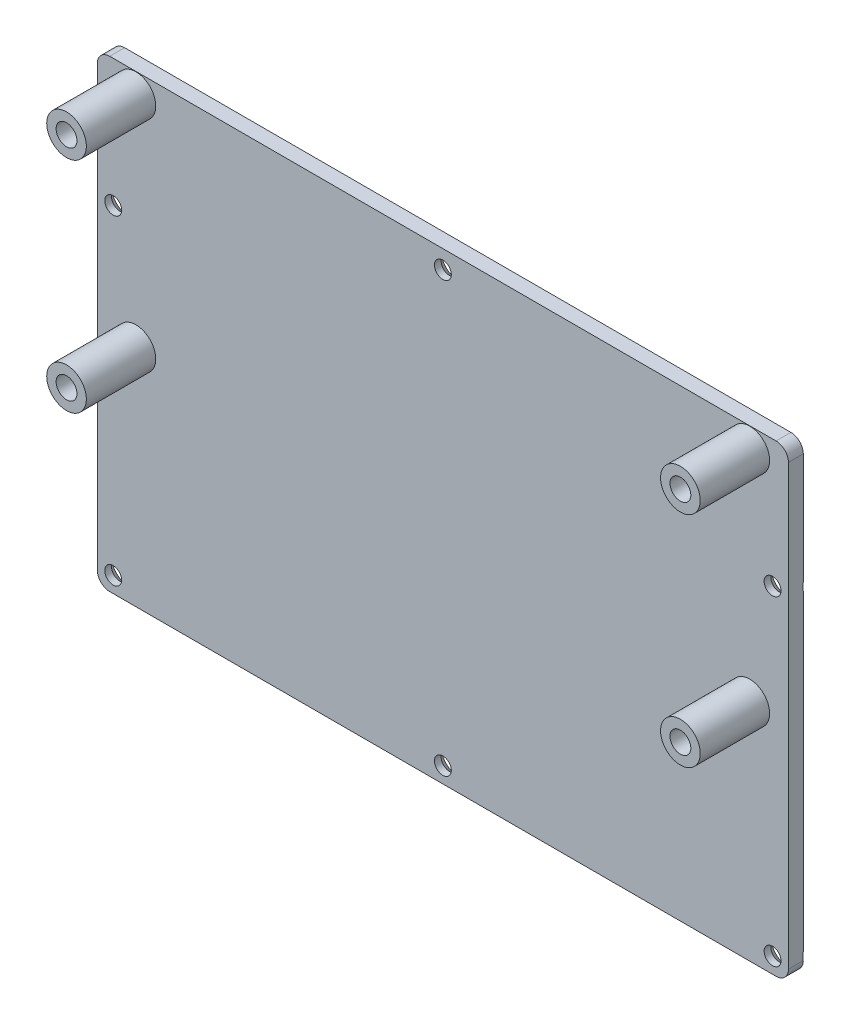
SolidWorks part; units mm, degrees
ref_plane "Front Plane" through (0, 0, 0) normal (0, 0, 1) x (1, 0, 0)
ref_plane "Top Plane" through (0, 0, 0) normal (0, 1, 0) x (1, 0, 0)
ref_plane "Right Plane" through (0, 0, 0) normal (1, 0, 0) x (0, 0, -1)
ref_plane "Plane1" through (0, 0, 0) normal (0, 0, -1) x (-1, 0, 0)
sketch "Sketch1" plane through (0, 0, 0) normal (0, 0, -1) x (-1, 0, 0)
  line L0 (-69.7, 93.82) -> (-69.7, 71.4262)
  line L1 (-69.7, 71.4262) -> (-69.7, 69.8138)
  line L2 (-69.7, 69.8138) -> (-69.7, 6.8062)
  line L3 (-69.7, 6.8062) -> (-69.7, 5.3)
  line L4 (-67.2, 2.8) -> (-65.6938, 2.8)
  line L5 (-65.6938, 2.8) -> (-0.8062, 2.8)
  line L6 (-0.8062, 2.8) -> (0.8062, 2.8)
  line L7 (0.8062, 2.8) -> (65.6938, 2.8)
  line L8 (65.6938, 2.8) -> (67.2, 2.8)
  line L9 (69.7, 5.3) -> (69.7, 6.8062)
  line L10 (69.7, 6.8062) -> (69.7, 69.8138)
  line L11 (69.7, 69.8138) -> (69.7, 71.4262)
  line L12 (69.7, 71.4262) -> (69.7, 93.82)
  line L13 (69.7, 93.82) -> (69.7, 96.32)
  line L14 (69.7, 96.32) -> (67.2, 96.32)
  line L15 (67.2, 96.32) -> (-67.2, 96.32)
  line L16 (-67.2, 96.32) -> (-69.7, 96.32)
  line L17 (-69.7, 96.32) -> (-69.7, 93.82)
  arc A0 (-69.7, 5.3) -> (-69.6973, 5.183) centre (-67.2, 5.3) ccw
  arc A1 (-67.317, 2.8027) -> (-69.6973, 5.183) centre (-67.2, 5.3) cw
  arc A2 (-67.317, 2.8027) -> (-67.2, 2.8) centre (-67.2, 5.3) ccw
  arc A3 (67.2, 2.8) -> (67.317, 2.8027) centre (67.2, 5.3) ccw
  arc A4 (69.6973, 5.183) -> (67.317, 2.8027) centre (67.2, 5.3) cw
  arc A5 (69.6973, 5.183) -> (69.7, 5.3) centre (67.2, 5.3) ccw
extrude "Boss-Extrude1" add sketch "Sketch1" against normal blind 3
ref_plane "Plane2" through (0, 70.62, 0) normal (0, 1, 0) x (1, 0, 0)
sketch "Sketch2" plane through (0, 70.62, 0) normal (0, 1, 0) x (1, 0, 0)
  line L0 (69.8002, 0.0002) -> (66.5, 0.0002)
  line L1 (66.5, 0.0002) -> (66.5, -3)
  line L2 (66.5, -3) -> (68.2, -3)
  line L3 (68.2, -3) -> (68.2, -1.6485)
  line L4 (68.2, -1.6485) -> (69.8002, 0.0002)
  line L5 (66.5, 0.0002) -> (66.5, -3) construction
revolve "Cut-Revolve1" cut sketch "Sketch2" angle 360 about L5
sketch "Sketch3" plane through (0, 70.62, 0) normal (0, 1, 0) x (1, 0, 0)
  line L0 (-63.1998, 0.0002) -> (-66.5, 0.0002)
  line L1 (-66.5, 0.0002) -> (-66.5, -3)
  line L2 (-66.5, -3) -> (-64.8, -3)
  line L3 (-64.8, -3) -> (-64.8, -1.6485)
  line L4 (-64.8, -1.6485) -> (-63.1998, 0.0002)
  line L5 (-66.5, 0.0002) -> (-66.5, -3) construction
revolve "Cut-Revolve2" cut sketch "Sketch3" angle 360 about L5
ref_plane "Plane3" through (0, 16, 0) normal (0, 1, 0) x (1, 0, 0)
sketch "Sketch4" plane through (0, 16, 0) normal (0, 1, 0) x (1, 0, 0)
  line L0 (-49, 4) -> (-56, 4)
  line L1 (-56, 4) -> (-56, 0)
  line L2 (-56, 0) -> (-49, 0)
  line L3 (-49, 0) -> (-49, 4)
  line L4 (-56, 4) -> (-56, -0.005) construction
revolve "Revolve1" add sketch "Sketch4" angle 360 about L4
sketch "Sketch5" plane through (0, 16, 0) normal (0, 1, 0) x (1, 0, 0)
  line L0 (63, 4) -> (56, 4)
  line L1 (56, 4) -> (56, 0)
  line L2 (56, 0) -> (63, 0)
  line L3 (63, 0) -> (63, 4)
  line L4 (56, 4) -> (56, -0.005) construction
revolve "Revolve2" add sketch "Sketch5" angle 360 about L4
ref_plane "Plane4" through (0, 82.62, 0) normal (0, 1, 0) x (1, 0, 0)
sketch "Sketch6" plane through (0, 82.62, 0) normal (0, 1, 0) x (1, 0, 0)
  line L0 (-49, 4) -> (-56, 4)
  line L1 (-56, 4) -> (-56, 0)
  line L2 (-56, 0) -> (-49, 0)
  line L3 (-49, 0) -> (-49, 4)
  line L4 (-56, 4) -> (-56, -0.005) construction
revolve "Revolve3" add sketch "Sketch6" angle 360 about L4
sketch "Sketch7" plane through (0, 82.62, 0) normal (0, 1, 0) x (1, 0, 0)
  line L0 (63, 4) -> (56, 4)
  line L1 (56, 4) -> (56, 0)
  line L2 (56, 0) -> (63, 0)
  line L3 (63, 0) -> (63, 4)
  line L4 (56, 4) -> (56, -0.005) construction
revolve "Revolve4" add sketch "Sketch7" angle 360 about L4
ref_plane "Plane5" through (0, 92.256, 0) normal (0, -1, 0) x (1, 0, 0)
sketch "Sketch8" plane through (0, 92.256, 0) normal (0, -1, 0) x (1, 0, 0)
  line L0 (65.91, 17) -> (61.91, 17)
  line L1 (61.91, 17) -> (61.91, 3)
  line L2 (61.91, 3) -> (65.91, 3)
  line L3 (65.91, 3) -> (65.91, 17)
  line L4 (61.91, 17.005) -> (61.91, 2.995) construction
revolve "Revolve5" add sketch "Sketch8" angle 360 about L4
sketch "Sketch9" plane through (0, 92.256, 0) normal (0, -1, 0) x (1, 0, 0)
  line L0 (-57.915, 17) -> (-61.915, 17)
  line L1 (-61.915, 17) -> (-61.915, 3)
  line L2 (-61.915, 3) -> (-57.915, 3)
  line L3 (-57.915, 3) -> (-57.915, 17)
  line L4 (-61.915, 17.005) -> (-61.915, 2.995) construction
revolve "Revolve6" add sketch "Sketch9" angle 360 about L4
ref_plane "Plane6" through (0, 48.06, 0) normal (0, -1, 0) x (1, 0, 0)
sketch "Sketch10" plane through (0, 48.06, 0) normal (0, -1, 0) x (1, 0, 0)
  line L0 (65.91, 17) -> (61.91, 17)
  line L1 (61.91, 17) -> (61.91, 3)
  line L2 (61.91, 3) -> (65.91, 3)
  line L3 (65.91, 3) -> (65.91, 17)
  line L4 (61.91, 17.005) -> (61.91, 2.995) construction
revolve "Revolve7" add sketch "Sketch10" angle 360 about L4
sketch "Sketch11" plane through (0, 48.06, 0) normal (0, -1, 0) x (1, 0, 0)
  line L0 (-57.915, 17) -> (-61.915, 17)
  line L1 (-61.915, 17) -> (-61.915, 3)
  line L2 (-61.915, 3) -> (-57.915, 3)
  line L3 (-57.915, 3) -> (-57.915, 17)
  line L4 (-61.915, 17.005) -> (-61.915, 2.995) construction
revolve "Revolve8" add sketch "Sketch11" angle 360 about L4
hole_wizard "CSK for #4 Flat Head Machine Screw (100)1" positions "Sketch13" profile "Sketch12" countersink size "#4" standard "ANSI Inch"
sketch "Sketch13" plane through (0, 0, 0) normal (0, 0, -1) x (-1, 0, 0)
  point P0 (66.5, 6)
  point P1 (0, 6)
  point P2 (-66.5, 6)
  point P3 (0, 92.62)
sketch "Sketch12" plane through (-66.5, 6, 0) normal (1, 0, 0) x (0, 1, 0)
  line L0 (0, 0) -> (0, 17)
  line L1 (0, 17) -> (1.7, 17)
  line L2 (1.7, 17) -> (1.7, 1.6485)
  line L3 (1.7, 1.6485) -> (3.3, 0)
  line L5 (3.3, 0) -> (0, 0)
  line L6 (-1.7, 1.6485) -> (-3.3, 0) construction
  line L11 (0, -6.35) -> (0, 107.95) construction
  dimension "Thru Hole Dia." = 3.4
  dimension "Thru Hole Depth" = 17
  dimension "Near C'Sink Dia." = 6.6
  dimension "Near C'Sink Angle" = 88.29
hole_wizard "#6 Clearance Hole1" positions "Sketch15" profile "Sketch14" hole size "#6" standard "ANSI Inch"
sketch "Sketch15" plane through (0, 0, 17) normal (0, 0, 1) x (1, 0, 0)
  point P0 (-61.915, 48.06)
  point P1 (61.91, 48.06)
  point P2 (-61.915, 92.256)
  point P3 (61.91, 92.256)
sketch "Sketch14" plane through (-61.915, 48.06, 17) normal (1, 0, 0) x (0, -1, 0)
  line L0 (0, 0) -> (0, 6)
  line L1 (0, 6) -> (2.1, 6)
  line L2 (2.1, 6) -> (2.1, 0)
  line L5 (2.1, 0) -> (0, 0)
  line L10 (0, 6) -> (-2.1, 6) construction
  line L11 (0, -6.35) -> (0, 107.95) construction
  dimension "Hole Dia." = 4.2
  dimension "Hole Depth" = 6
  dimension "Drill Angle" = 180
hole_wizard "3/8 Clearance Hole1" positions "Sketch17" profile "Sketch16" hole size "3/8" standard "ANSI Inch"
sketch "Sketch17" plane through (0, 0, -4) normal (0, 0, -1) x (-1, 0, 0)
  point P0 (-56, 82.62)
  point P1 (56, 82.62)
  point P2 (-56, 16)
  point P3 (56, 16)
sketch "Sketch16" plane through (56, 82.62, -4) normal (1, 0, 0) x (0, 1, 0)
  line L0 (0, 0) -> (0, 0.79)
  line L1 (0, 0.79) -> (5.1, 0.79)
  line L2 (5.1, 0.79) -> (5.1, 0)
  line L5 (5.1, 0) -> (0, 0)
  line L10 (0, 0.79) -> (-5.1, 0.79) construction
  line L11 (0, -6.35) -> (0, 107.95) construction
  dimension "Hole Dia." = 10.2
  dimension "Hole Depth" = 0.79
  dimension "Drill Angle" = 180
fillet "Fillet1" radius 1.5 4 edges at (-49, 82.62, -4) (63, 16, -4) (63, 82.62, -4) (-49, 16, -4)
fillet "Fillet2" radius 2.5 2 edges at (69.7, 96.32, 1.5) (-69.7, 96.32, 1.5)
